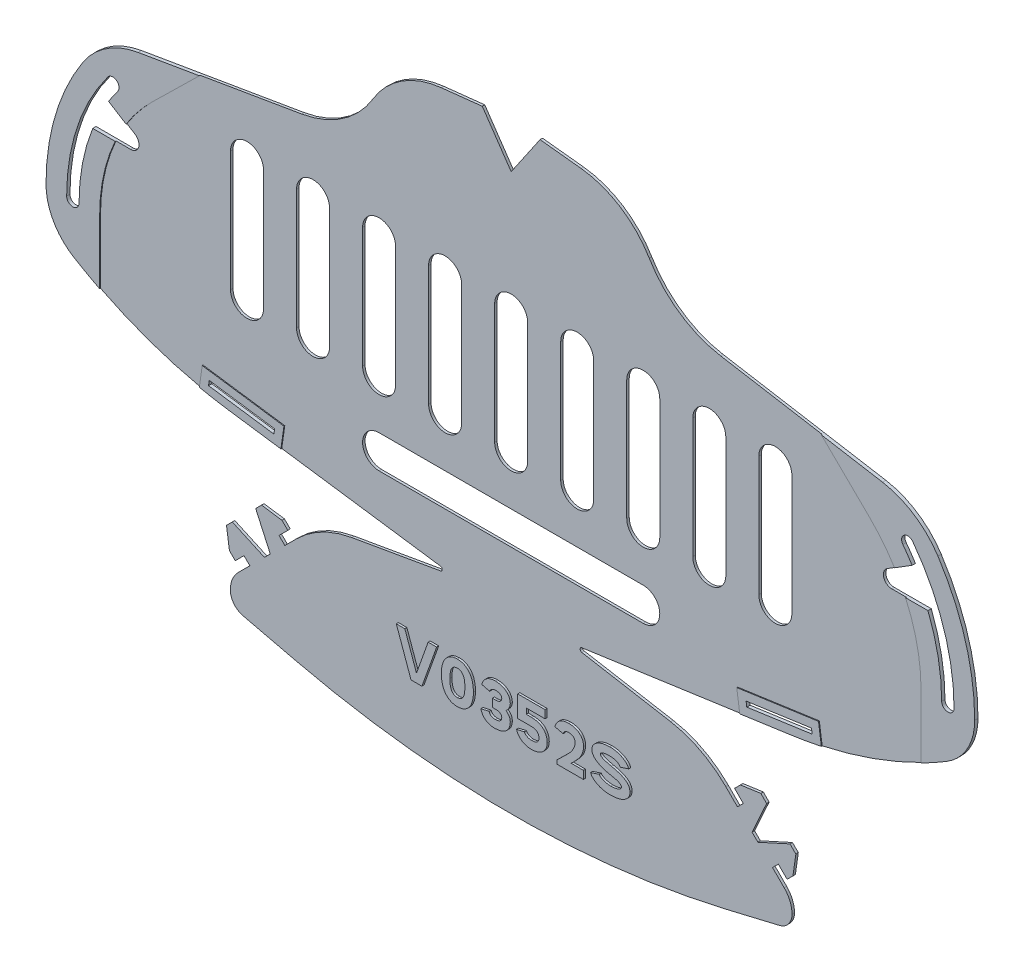
SolidWorks part; units mm, degrees
ref_plane "Front Plane" through (0, 0, 0) normal (0, 0, 1) x (1, 0, 0)
ref_plane "Top Plane" through (0, 0, 0) normal (0, 1, 0) x (1, 0, 0)
ref_plane "Right Plane" through (0, 0, 0) normal (1, 0, 0) x (0, 0, -1)
sketch "Sketch1" plane through (0, 0, 0) normal (0, 0, 1) x (1, 0, 0)
  line L0 (0, 0) -> (0, -145) construction
  line L1 (-14, -102) -> (14, -102) construction
  line L2 (-112.5, -69) -> (112.5, -69) construction
  line L3 (0, -10.2352) -> (-7, 0)
  line L4 (0, -10.2352) -> (7, 0)
  line L5 (7, 0) -> (16.9419, -1.0768)
  line L6 (-90.1804, -30.1909) -> (-50.7439, -23.5)
  line L7 (90.1804, -30.1909) -> (50.7439, -23.5)
  line L8 (-14, -102) -> (-68.2662, -94.2919)
  line L9 (-7, 0) -> (-16.9419, -1.0768)
  line L10 (14, -102) -> (68.2662, -94.2919)
  line L11 (-103.5977, -39) -> (-103.5977, -69) construction
  line L12 (-14, -102) -> (-38.6266, -106.305)
  line L13 (-52, -113.2546) -> (-54.8283, -116.0832)
  line L14 (52, -113.2546) -> (54.8283, -116.0832)
  line L15 (14, -102) -> (38.6266, -106.305)
  line L16 (-54.8283, -116.0832) -> (-56.2426, -114.669)
  line L17 (-56.2426, -114.669) -> (-54.1214, -112.5476)
  line L18 (-54.1214, -112.5476) -> (-55.5356, -111.1334)
  line L19 (-55.5356, -111.1334) -> (-60.4854, -110.4265)
  line L20 (-60.4854, -110.4265) -> (-68.9703, -118.9122)
  line L21 (-64.7275, -123.1546) -> (-63.3132, -124.5688)
  line L22 (-63.3132, -124.5688) -> (-66.1415, -127.3973)
  line L23 (-64.7275, -123.1546) -> (-66.8487, -125.2761)
  line L24 (-66.8487, -125.2761) -> (-68.263, -123.8619)
  line L25 (-68.9703, -118.9122) -> (-68.263, -123.8619)
  line L26 (68.9703, -118.9122) -> (68.263, -123.8619)
  line L27 (66.8487, -125.2761) -> (68.263, -123.8619)
  line L28 (64.7275, -123.1546) -> (66.8487, -125.2761)
  line L29 (63.3132, -124.5688) -> (66.1415, -127.3973)
  line L30 (64.7275, -123.1546) -> (63.3132, -124.5688)
  line L31 (60.4854, -110.4265) -> (68.9703, -118.9122)
  line L32 (55.5356, -111.1334) -> (60.4854, -110.4265)
  line L33 (54.1214, -112.5476) -> (55.5356, -111.1334)
  line L34 (56.2426, -114.669) -> (54.1214, -112.5476)
  line L35 (54.8283, -116.0832) -> (56.2426, -114.669)
  line L36 (-64.9691, -135.8852) -> (-52.4361, -138.8607)
  line L37 (64.9691, -135.8852) -> (52.4361, -138.8607)
  line L38 (-68.9703, -118.9122) -> (-64.7275, -123.1546) construction
  line L39 (-60.4854, -110.4265) -> (-56.2426, -114.669) construction
  arc A0 (-16.9419, -1.0768) -> (-33.4614, -11.6696) centre (-14.5729, -22.9489) ccw
  arc A1 (-33.4614, -11.6696) -> (-50.7439, -23.5) centre (-54.9257, 1.1478) cw
  arc A2 (-103.5977, -39) -> (-90.1804, -30.1909) centre (-86.8349, -49.9091) cw
  arc A3 (-112.5, -69) -> (-103.5977, -39) centre (-57.5, -69) cw
  arc A4 (112.5, -69) -> (103.5977, -39) centre (57.5, -69) ccw
  arc A5 (103.5977, -39) -> (90.1804, -30.1909) centre (86.8349, -49.9091) ccw
  arc A6 (16.9419, -1.0768) -> (33.4614, -11.6696) centre (14.5729, -22.9489) cw
  arc A7 (33.4614, -11.6696) -> (50.7439, -23.5) centre (54.9257, 1.1478) ccw
  arc A8 (-112.5, -69) -> (-105.7111, -81) centre (-98.5, -69) ccw
  arc A9 (-105.7111, -81) -> (-68.2662, -94.2919) centre (-54.2032, 4.7143) ccw
  arc A10 (112.5, -69) -> (105.7111, -81) centre (98.5, -69) cw
  arc A11 (105.7111, -81) -> (68.2662, -94.2919) centre (54.2032, 4.7143) cw
  arc A12 (-38.6266, -106.305) -> (-52, -113.2546) centre (-34.3216, -130.9315) ccw
  arc A13 (38.6266, -106.305) -> (52, -113.2546) centre (34.3216, -130.9315) cw
  arc A14 (-66.1415, -127.3973) -> (-68.0451, -131.9933) centre (-61.5451, -131.9933) ccw
  arc A15 (-68.0451, -131.9933) -> (-64.9691, -135.8852) centre (-64.0451, -131.9933) ccw
  arc A16 (68.0451, -131.9933) -> (64.9691, -135.8852) centre (64.0451, -131.9933) cw
  arc A17 (66.1415, -127.3973) -> (68.0451, -131.9933) centre (61.5451, -131.9933) cw
  arc A19 (-52.4361, -138.8607) -> (0, -145) centre (0, 82) ccw
  arc A20 (52.4361, -138.8607) -> (0, -145) centre (0, 82) cw
  point P8 (0, -102)
  point P11 (0, -69)
  dimension "D5" = 55
  dimension "D11" = 20
  dimension "D13" = 25
  dimension "D16" = 14
  dimension "D15" = 22
  dimension "D18" = 100
  dimension "D22" = 25
  dimension "D31" = 6.5
  dimension "D32" = 4
  dimension "D34" = 227
  dimension "D1" = 145
  dimension "D2" = 28
  dimension "D3" = 43
  dimension "D4" = 76
  dimension "D6" = 225
  dimension "D7" = 14
  dimension "D8" = 12.4
  dimension "D9" = 10
  dimension "D10" = 30
  dimension "D12" = 40
  dimension "D14" = 45.5
  dimension "D17" = 12
  dimension "D19" = 18
  dimension "D20" = 25
  dimension "D21" = 4
  dimension "D23" = 38
  dimension "D24" = 2
  dimension "D25" = 3
  dimension "D26" = 2
  dimension "D27" = 18
  dimension "D29" = 8
  dimension "D30" = 4
extrude "Main Shape" add sketch "Sketch1" along normal blind 0.6
sketch "Sketch2" plane through (0, 0, 0.6) normal (0, 0, 1) x (1, 0, 0)
  line L0 (0, -55) -> (0, 55) construction
  arc A0 (-96.3, -39.9) -> (-106, -69) centre (-57.5, -69) ccw construction
  arc A1 (-97.5, -39) -> (-107.5, -69) centre (-57.5, -69) ccw
  arc A2 (-95.1, -40.8) -> (-104.5, -69) centre (-57.5, -69) ccw
  arc A3 (-95.1, -40.8) -> (-97.5, -39) centre (-96.3, -39.9) ccw
  arc A4 (-107.5, -69) -> (-104.5, -69) centre (-106, -69) ccw
  arc A6 (-103.5977, -39) -> (-112.5, -69) centre (-57.5, -69) ccw construction
  arc A7 (96.3, -39.9) -> (106, -69) centre (57.5, -69) cw construction
  arc A8 (97.5, -39) -> (107.5, -69) centre (57.5, -69) cw
  arc A9 (95.1, -40.8) -> (104.5, -69) centre (57.5, -69) cw
  arc A10 (95.1, -40.8) -> (97.5, -39) centre (96.3, -39.9) cw
  arc A11 (107.5, -69) -> (104.5, -69) centre (106, -69) cw
  point P3 (-103.5111, -53.663)
  point P19 (103.5111, -53.663)
  dimension "D1" = 5
  dimension "D2" = 1.5
extrude "Elastic Attachment Points" cut sketch "Sketch2" against normal through all
sketch "Sketch7" plane through (0, 0, 0.6) normal (0, 0, 1) x (1, 0, 0)
  line L0 (-99.5, -69) -> (-99.5, -84.4384)
  line L1 (-86.8939, -39) -> (-75.3319, -27.6717)
  line L2 (-50.7439, -23.5) -> (-90.1804, -30.1909) construction
  line L3 (-75.3319, -27.6717) -> (-90.1804, -30.1909)
  line L4 (0, -55) -> (0, 55) construction
  line L5 (75.3319, -27.6717) -> (90.1804, -30.1909)
  line L6 (86.8939, -39) -> (75.3319, -27.6717)
  line L7 (99.5, -69) -> (99.5, -84.4384)
  arc A0 (-99.5, -69) -> (-86.8939, -39) centre (-57.5, -69) cw
  arc A1 (-95.1, -40.8) -> (-104.5, -69) centre (-57.5, -69) ccw construction
  arc A2 (-105.7111, -81) -> (-68.2662, -94.2919) centre (-54.2032, 4.7143) ccw construction
  arc A3 (-112.5, -69) -> (-105.7111, -81) centre (-98.5, -69) ccw construction
  arc A4 (-103.5977, -39) -> (-112.5, -69) centre (-57.5, -69) ccw construction
  arc A5 (-90.1804, -30.1909) -> (-103.5977, -39) centre (-86.8349, -49.9091) ccw construction
  arc A6 (-105.7111, -81) -> (-99.5, -84.4384) centre (-54.2032, 4.7143) ccw
  arc A7 (-112.5, -69) -> (-105.7111, -81) centre (-98.5, -69) ccw
  arc A8 (-103.5977, -39) -> (-112.5, -69) centre (-57.5, -69) ccw
  arc A9 (-90.1804, -30.1909) -> (-103.5977, -39) centre (-86.8349, -49.9091) ccw
  arc A10 (90.1804, -30.1909) -> (103.5977, -39) centre (86.8349, -49.9091) cw
  arc A11 (103.5977, -39) -> (112.5, -69) centre (57.5, -69) cw
  arc A12 (112.5, -69) -> (105.7111, -81) centre (98.5, -69) cw
  arc A13 (105.7111, -81) -> (99.5, -84.4384) centre (54.2032, 4.7143) cw
  arc A14 (99.5, -69) -> (86.8939, -39) centre (57.5, -69) ccw
  arc A15 (-107.5, -69) -> (-104.5, -69) centre (-106, -69) ccw construction
  arc A16 (-95.1, -40.8) -> (-97.5, -39) centre (-96.3, -39.9) ccw construction
  arc A17 (-97.5, -39) -> (-107.5, -69) centre (-57.5, -69) ccw construction
  arc A18 (-107.5, -69) -> (-104.5, -69) centre (-106, -69) ccw
  arc A19 (-95.1, -40.8) -> (-97.5, -39) centre (-96.3, -39.9) ccw
  arc A20 (-95.1, -40.8) -> (-104.5, -69) centre (-57.5, -69) ccw
  arc A21 (-97.5, -39) -> (-107.5, -69) centre (-57.5, -69) ccw
  arc A22 (104.5, -69) -> (107.5, -69) centre (106, -69) ccw construction
  arc A23 (97.5, -39) -> (95.1, -40.8) centre (96.3, -39.9) ccw construction
  arc A24 (104.5, -69) -> (95.1, -40.8) centre (57.5, -69) ccw construction
  arc A25 (107.5, -69) -> (97.5, -39) centre (57.5, -69) ccw construction
  arc A26 (104.5, -69) -> (107.5, -69) centre (106, -69) ccw
  arc A27 (97.5, -39) -> (95.1, -40.8) centre (96.3, -39.9) ccw
  arc A28 (104.5, -69) -> (95.1, -40.8) centre (57.5, -69) ccw
  arc A29 (107.5, -69) -> (97.5, -39) centre (57.5, -69) ccw
  dimension "D1" = 5
extrude "Reinforced Attachment Points" add sketch "Sketch7" along normal blind 0.2
sketch "Sketch6" plane through (0, 0, 0.6) normal (0, 0, 1) x (1, 0, 0)
  line L0 (-73.1225, -91.5821) -> (-57.2815, -93.8322)
  line L1 (-57.2815, -93.8322) -> (-57.1127, -92.6441)
  line L2 (-57.1127, -92.6441) -> (-72.9537, -90.394)
  line L3 (-72.9537, -90.394) -> (-73.1225, -91.5821)
  line L4 (-68.2662, -94.2919) -> (-14, -102) construction
  line L5 (-65.0332, -91.519) -> (-65.202, -92.7071) construction
  line L13 (0, -0.44) -> (0, 0.44) construction
  line L14 (65.0332, -91.519) -> (65.202, -92.7071) construction
  line L15 (73.1225, -91.5821) -> (72.9537, -90.394)
  line L16 (57.1127, -92.6441) -> (57.2815, -93.8322)
  line L22 (57.1127, -92.6441) -> (72.9537, -90.394)
  line L24 (73.1225, -91.5821) -> (57.2815, -93.8322)
  dimension "D1" = 2
  dimension "D2" = 16
  dimension "D3" = 52
  dimension "D4" = 1.2
extrude "Tab Slits" cut sketch "Sketch6" against normal through all
sketch "Sketch9" plane through (0, 0, 0.6) normal (0, 0, 1) x (1, 0, 0)
  line L4 (-57.2815, -93.8322) -> (-57.1127, -92.6441) construction
  line L5 (-73.1225, -91.5821) -> (-57.2815, -93.8322) construction
  line L6 (-72.9537, -90.394) -> (-73.1225, -91.5821) construction
  line L7 (-57.1127, -92.6441) -> (-72.9537, -90.394) construction
  line L12 (-57.2815, -93.8322) -> (-57.1127, -92.6441)
  line L13 (-73.1225, -91.5821) -> (-57.2815, -93.8322)
  line L14 (-72.9537, -90.394) -> (-73.1225, -91.5821)
  line L15 (-57.1127, -92.6441) -> (-72.9537, -90.394)
  line L16 (-55.5826, -96.0935) -> (-54.8513, -90.9452)
  line L17 (-68.2662, -94.2919) -> (-14, -102) construction
  line L18 (-54.8513, -90.9452) -> (-74.6526, -88.1326)
  line L19 (-74.6526, -88.1326) -> (-75.3475, -93.0248)
  line L20 (-68.2662, -94.2919) -> (-55.5826, -96.0935)
  line L21 (0, -0.44) -> (0, 0.44) construction
  line L22 (68.2662, -94.2919) -> (55.5826, -96.0935)
  line L23 (74.6526, -88.1326) -> (75.3475, -93.0248)
  line L24 (54.8513, -90.9452) -> (74.6526, -88.1326)
  line L25 (55.5826, -96.0935) -> (54.8513, -90.9452)
  line L26 (57.1127, -92.6441) -> (72.9537, -90.394)
  line L27 (72.9537, -90.394) -> (73.1225, -91.5821)
  line L28 (73.1225, -91.5821) -> (57.2815, -93.8322)
  line L29 (57.2815, -93.8322) -> (57.1127, -92.6441)
  arc A0 (-99.5, -84.4384) -> (-68.2662, -94.2919) centre (-54.2032, 4.7143) ccw construction
  arc A1 (-75.3475, -93.0248) -> (-68.2662, -94.2919) centre (-54.2032, 4.7143) ccw
  arc A2 (75.3475, -93.0248) -> (68.2662, -94.2919) centre (54.2032, 4.7143) cw
  dimension "D1" = 2
  dimension "D2" = 2
  dimension "D3" = 2
extrude "Reinforced Tab Slits" add sketch "Sketch9" along normal blind 0.2
sketch "Sketch11" plane through (0, 0, 0.6) normal (0, 0, 1) x (1, 0, 0)
  line L0 (-67.5562, -117.4979) -> (-59.7778, -121.0331)
  line L1 (-60.4854, -110.4265) -> (-68.9703, -118.9122) construction
  line L2 (-59.7778, -121.0331) -> (-58.3637, -119.6188)
  line L3 (-58.3637, -119.6188) -> (-61.8996, -111.8408)
  line L4 (-61.8996, -111.8408) -> (-67.5562, -117.4979)
  line L6 (-58.3637, -119.6188) -> (-54.8283, -116.0832) construction
  line L7 (-59.7778, -121.0331) -> (-63.3132, -124.5688) construction
  line L10 (0, -0.44) -> (0, 0.44) construction
  line L11 (59.7778, -121.0331) -> (63.3132, -124.5688) construction
  line L12 (58.3637, -119.6188) -> (54.8283, -116.0832) construction
  line L13 (61.8996, -111.8408) -> (67.5562, -117.4979)
  line L14 (58.3637, -119.6188) -> (61.8996, -111.8408)
  line L15 (59.7778, -121.0331) -> (58.3637, -119.6188)
  line L16 (67.5562, -117.4979) -> (59.7778, -121.0331)
  dimension "D1" = 2
  dimension "D2" = 2
  dimension "D3" = 5
extrude "Tab Flex Relief" cut sketch "Sketch11" against normal through all both and the other way through all
sketch "Sketch3" plane through (0, 0, 0.6) normal (0, 0, 1) x (1, 0, 0)
  line L3 (0, -10.2352) -> (0, -145) construction
  line L4 (-106, -69) -> (-96.3, -69) construction
  line L5 (-96.3, -69) -> (-96.3, -39.9) construction
  line L427 (0, -39.9) -> (0, -69) construction
  line L428 (4, -39.9) -> (4, -69)
  line L429 (-4, -39.9) -> (-4, -69)
  line L444 (-16, -39.9) -> (-16, -69) construction
  line L447 (-12, -39.9) -> (-12, -69)
  line L450 (-20, -39.9) -> (-20, -69)
  line L451 (-32, -39.9) -> (-32, -69) construction
  line L455 (-28, -39.9) -> (-28, -69)
  line L456 (-36, -39.9) -> (-36, -69)
  line L836 (-32, -85) -> (32, -85) construction
  line L837 (-32, -81) -> (32, -81)
  line L838 (-32, -89) -> (32, -89)
  line L839 (-64, -73) -> (64, -73) construction
  line L933 (-48, -39.9) -> (-48, -69) construction
  line L934 (-44, -39.9) -> (-44, -69)
  line L935 (-52, -39.9) -> (-52, -69)
  line L936 (-64, -39.9) -> (-64, -69) construction
  line L937 (-60, -39.9) -> (-60, -69)
  line L938 (-68, -39.9) -> (-68, -69)
  line L939 (16, -39.9) -> (16, -69) construction
  line L940 (12, -39.9) -> (12, -69)
  line L941 (20, -39.9) -> (20, -69)
  line L942 (32, -39.9) -> (32, -69) construction
  line L943 (28, -39.9) -> (28, -69)
  line L944 (36, -39.9) -> (36, -69)
  line L945 (48, -39.9) -> (48, -69) construction
  line L946 (44, -39.9) -> (44, -69)
  line L947 (52, -39.9) -> (52, -69)
  line L948 (64, -39.9) -> (64, -69) construction
  line L949 (60, -39.9) -> (60, -69)
  line L950 (68, -39.9) -> (68, -69)
  arc A2 (-52.4361, -138.8607) -> (52.4361, -138.8607) centre (0, 82) ccw construction
  arc A21 (4, -39.9) -> (-4, -39.9) centre (0, -39.9) ccw
  arc A22 (-4, -69) -> (4, -69) centre (0, -69) ccw
  arc A23 (-12, -39.9) -> (-20, -39.9) centre (-16, -39.9) ccw
  arc A24 (-20, -69) -> (-12, -69) centre (-16, -69) ccw
  arc A25 (-28, -39.9) -> (-36, -39.9) centre (-32, -39.9) ccw
  arc A26 (-36, -69) -> (-28, -69) centre (-32, -69) ccw
  arc A27 (-44, -39.9) -> (-52, -39.9) centre (-48, -39.9) ccw
  arc A28 (-52, -69) -> (-44, -69) centre (-48, -69) ccw
  arc A29 (-60, -39.9) -> (-68, -39.9) centre (-64, -39.9) ccw
  arc A30 (-68, -69) -> (-60, -69) centre (-64, -69) ccw
  arc A31 (12, -39.9) -> (20, -39.9) centre (16, -39.9) cw
  arc A32 (20, -69) -> (12, -69) centre (16, -69) cw
  arc A33 (28, -39.9) -> (36, -39.9) centre (32, -39.9) cw
  arc A34 (36, -69) -> (28, -69) centre (32, -69) cw
  arc A35 (44, -39.9) -> (52, -39.9) centre (48, -39.9) cw
  arc A36 (52, -69) -> (44, -69) centre (48, -69) cw
  arc A37 (60, -39.9) -> (68, -39.9) centre (64, -39.9) cw
  arc A38 (68, -69) -> (60, -69) centre (64, -69) cw
  arc A39 (-32, -81) -> (-32, -89) centre (-32, -85) ccw
  arc A40 (32, -89) -> (32, -81) centre (32, -85) ccw
  point P3 (-16, -54.45)
  point P18 (-32, -54.45)
  point P30 (-48, -54.45)
  point P37 (-64, -54.45)
  point P43 (16, -54.45)
  point P50 (32, -54.45)
  point P57 (48, -54.45)
  point P64 (64, -54.45)
  point P71 (0, -85)
  point P414 (0, -54.45)
  dimension "D5" = 8
  dimension "D1" = 8
  dimension "D2" = 5
  dimension "D3" = 8
  dimension "D4" = 8
extrude "Breathing Slits" cut sketch "Sketch3" against normal through all
sketch "Sketch8" plane through (0, 0, 0.6) normal (0, 0, 1) x (1, 0, 0)
  line L0 (-67.0266, -128.5) -> (67.0266, -128.5) construction
  line L1 (0, -10.2352) -> (0, -145) construction
  arc A0 (-52.4361, -138.8607) -> (52.4361, -138.8607) centre (0, 82) ccw construction
  arc A1 (-66.1415, -127.3973) -> (-68.0451, -131.9933) centre (-61.5451, -131.9933) ccw construction
  text T0 "<b>V0352S</b>\r\n" font "Double Porter 3" height 10
  point P9 (0, -128.5)
  dimension "D2" = 16.5
extrude "Version Number" add sketch "Sketch8" along normal blind 0.5
fillet "Fillet1" radius 0.5 2 edges at (-14, -102, 0.3) (14, -102, 0.3)
sketch "Sketch12" plane through (0, 0, 0.8) normal (0, 0, 1) x (1, 0, 0)
  line L0 (-97.3304, -44.0493) -> (-91.1089, -47.9466)
  line L1 (-97.3304, -44.0493) -> (-88.4671, -29.9002) construction
  line L2 (-75.3319, -27.6717) -> (-90.1804, -30.1909) construction
  line L3 (-101.1729, -51.6312) -> (-92.1729, -51.6415)
  line L4 (0, -0.44) -> (0, 0.44) construction
  line L5 (97.3304, -44.0493) -> (88.4671, -29.9002) construction
  line L6 (101.1729, -51.6312) -> (92.1729, -51.6415)
  line L7 (97.3304, -44.0493) -> (91.1089, -47.9466)
  arc A0 (-95.1, -40.8) -> (-104.5, -69) centre (-57.5, -69) ccw construction
  arc A1 (-92.1729, -51.6415) -> (-91.1089, -47.9466) centre (-92.1706, -49.6415) ccw
  arc A2 (-97.3304, -44.0493) -> (-101.1729, -51.6312) centre (-57.5, -69) ccw
  arc A3 (97.3304, -44.0493) -> (101.1729, -51.6312) centre (57.5, -69) cw
  arc A4 (92.1729, -51.6415) -> (91.1089, -47.9466) centre (92.1706, -49.6415) cw
  dimension "D4" = 2
  dimension "D1" = 24.9507
  dimension "D2" = 8.5
  dimension "D3" = 9
extrude "Cut-Extrude1" cut sketch "Sketch12" against normal through all both and the other way through all
